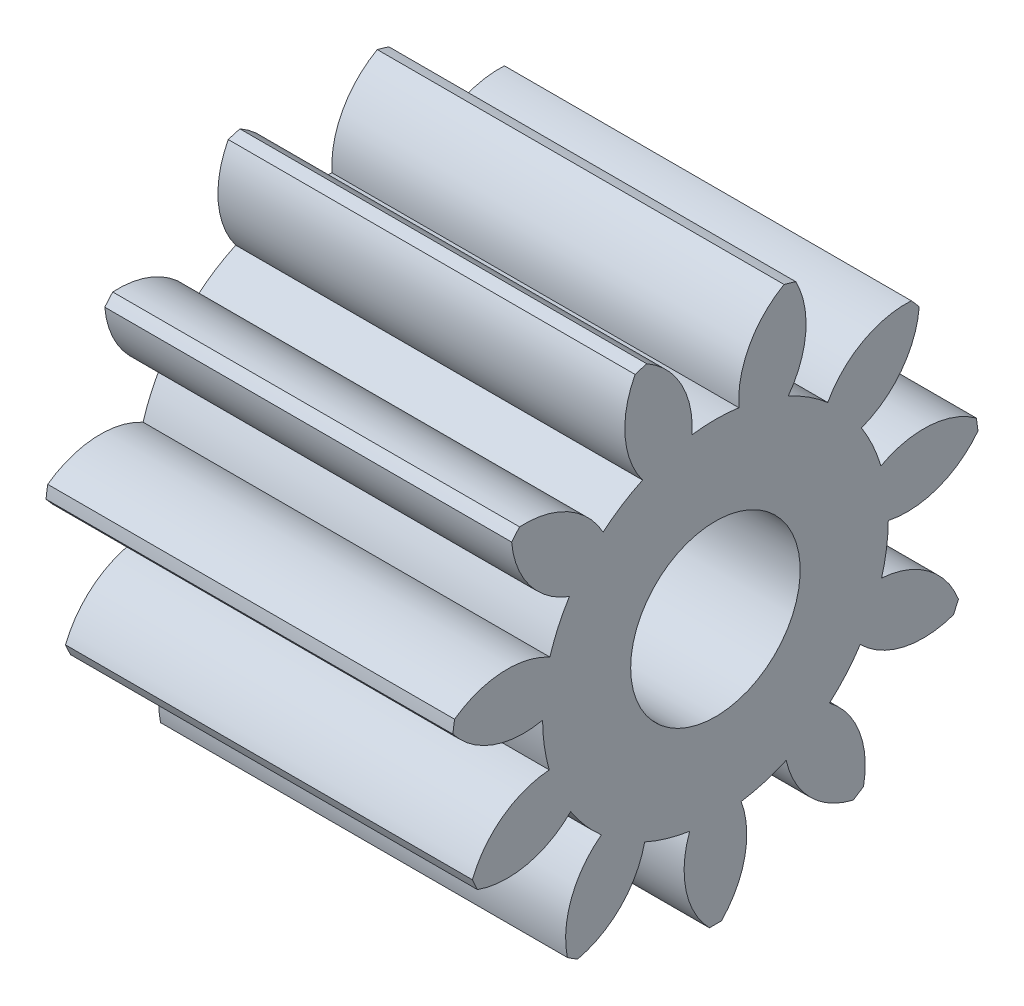
SolidWorks part; units mm, degrees
ref_plane "Plane1" through (0, 0, 0) normal (0, 0, 1) x (1, 0, 0)
ref_plane "Plane2" through (0, 0, 0) normal (0, 1, 0) x (1, 0, 0)
ref_plane "Plane3" through (0, 0, 0) normal (1, 0, 0) x (0, 0, -1)
other "Configuration Table"
sketch "HoldingSke" plane through (0, 0, 0) normal (0, 1, 0) x (1, 0, 0)
  line L0 (0, 0) -> (1.636, -0.318)
  line L1 (-15, 0) -> (100, 0) construction
  line L2 (0, 0) -> (-2.1039, 2.3779)
  line L3 (0, 0) -> (-11.863, 4.5341)
  line L4 (0, 0) -> (8.4773, 1.6478)
  line L5 (0, 0) -> (-46.8476, -17.4728)
  line L6 (0, 0) -> (-4.9738, -3.3558)
  line L7 (-2.1039, 2.3779) -> (8.6586, 51.206)
  line L8 (-76.2, 54.61) -> (-75.7, 54.61)
  line L9 (-71.009, 38.7566) -> (-53.1078, 45.2721)
  line L10 (-76.2, 71.12) -> (104.1128, 71.12)
  line L11 (0, 0) -> (-6, 0)
  line L12 (-76.2, 101.6) -> (-76.177, 101.6)
  line L13 (24.9733, 27.94) -> (52.9518, 28.4284)
  line L14 (24.9733, 27.94) -> (24.9743, 27.94)
  line L15 (24.9733, 27.94) -> (100.4006, 29.5858)
  line L16 (-63.627, -0.6) -> (-12.827, -0.6)
  circle A0 centre (0, 0) radius 1.5
  circle A1 centre (0, 0) radius 2.549
  circle A2 centre (0, 0) radius 37.5
  circle A3 centre (0, 0) radius 1.25
  dimension "MHD" = 5.098
  dimension "Hub_dia" = 75
  dimension "Bore" = 3
  dimension "MBD" = 2.5
  dimension "Num_teeth" = 11
  dimension "Pitch" = 1.6667
  dimension "Overall_len" = 50
  dimension "Show_teeth" = 11
  dimension "Thickness" = 6
  dimension "OAL" = 50.0002
  dimension "T_dim" = 0.5
  dimension "Ap" = 20
  dimension "H" = 19.05
  dimension "Pitch_radius" = 180.3128
  dimension "Width" = 6
  dimension "Backlash" = 0.023
  dimension "Addendum_fac" = 1
  dimension "Dedendum_fac" = 1.25
  dimension "Clearance_fac" = 0.25
  dimension "Dedendum_add" = 0.001
  dimension "Module" = 0.6
sketch "BasProSke" plane through (0, 0, 0) normal (0, 1, 0) x (1, 0, 0)
  line L0 (-10, 0) -> (60, 0) construction
  line L1 (0, 0) -> (0, 3.9)
  line L2 (0, 0) -> (6, 0)
  line L3 (6, 0) -> (6, 3.9)
  line L4 (6, 3.9) -> (0, 3.9)
  dimension "Thickness" = 6
  dimension "Diameter" = 7.8
revolve "Base-Revolve" add sketch "BasProSke" angle 360 about L0
sketch "TooCutSke" plane through (0, 0, 0) normal (1, 0, 0) x (0, 0, -1)
  line L1 (0, 0) -> (0, 107) construction
  line L2 (0, 0) -> (-0.5098, 3.2604) construction
  line L3 (0, 0) -> (-1.8436, 6.2788) construction
  line L4 (-0.5098, 3.2604) -> (-0.9218, 3.1394) construction
  arc A0 (0.3459, 2.5254) -> (-0.3459, 2.5254) centre (0, 0) ccw
  arc A1 (1.0446, 3.7839) -> (-1.0446, 3.7839) centre (0, 0) ccw
  circle A2 centre (0, 0) radius 3.3 construction
  circle A3 centre (0, 0) radius 3.101 construction
  arc A4 (-0.3459, 2.5254) -> (-1.0446, 3.7839) centre (-1.6627, 2.6175) ccw
  arc A5 (1.0446, 3.7839) -> (0.3459, 2.5254) centre (1.6627, 2.6175) ccw
  dimension "Root_dia" = 5.098
  dimension "Overcut_dia" = 7.8508
  dimension "Pitch_dia" = 6.6
  dimension "Base_dia" = 6.202
  dimension "Flank_rad" = 1.32
  dimension "Half_ang" = 16.364
  dimension "Half_CT" = 0.4294
extrude "ToothCut" cut sketch "TooCutSke" along normal through all
fillet "Breaks" [suppressed] radius 0.012
fillet "RootFillets" [suppressed] radius 0.151
pattern_circular "TeethCuts" count 11 over 360 about axis through (0, 0, 0) along (1, 0, 0) of "ToothCut", "RootFillets", "Breaks"
sketch "HubNeaOneSke" plane through (0, 0, 0) normal (-1, 0, 0) x (0, 0, 1)
  circle A0 centre (0, 0) radius 2.549
  dimension "Diameter" = 5.098
extrude "HubNearOne" [suppressed] add sketch "HubNeaOneSke" along normal blind 44.0002
sketch "HubNeaBotSke" plane through (0, 0, 0) normal (-1, 0, 0) x (0, 0, 1)
  circle A0 centre (0, 0) radius 2.549
  dimension "Diameter" = 5.098
extrude "HubNearBoth" [suppressed] add sketch "HubNeaBotSke" along normal blind 22.0001
ref_plane "FarPln" through (6, 0, 0) normal (1, 0, 0) x (0, 0, -1)
sketch "HubFarSke" plane through (6, 0, 0) normal (1, 0, 0) x (0, 0, -1)
  circle A0 centre (0, 0) radius 2.549
  dimension "Diameter" = 5.098
extrude "HubFar" [suppressed] add sketch "HubFarSke" along normal blind 22.0001
sketch "BorSke" plane through (0, 0, 0) normal (1, 0, 0) x (0, 0, -1)
  circle A0 centre (0, 0) radius 1.25
  dimension "Diameter" = 2.5
extrude "Bore" cut sketch "BorSke" along normal mid plane 100.0003
sketch "KeySke" plane through (0, 0, 0) normal (1, 0, 0) x (0, 0, -1)
  line L0 (-0.6, 0) -> (-0.6, 1.75)
  line L1 (-0.6, 1.75) -> (0.6, 1.75)
  line L2 (0.6, 1.75) -> (0.6, 0)
  line L3 (0, 0) -> (0, 34) construction
  line L4 (-0.6, 0) -> (0.6, 0)
  dimension "Offset" = 1.75
  dimension "Width" = 1.2
extrude "Keyway" [suppressed] cut sketch "KeySke" along normal mid plane 100.0003
pattern_circular "Keyway2" [suppressed] count 2 every 90 about axis through (-10, 0, 0) along (1, 0, 0)
equation "' \"Module@HoldingSke\" = 6.35"
equation "' \"Num_teeth@HoldingSke\" = 12"
equation "' \"Ap@HoldingSke\" =  20"
equation "' \"Ap@HoldingSke\" = 20"
equation "' \"Width@HoldingSke\" = 0.5 * 25.4"
equation "' \"Hub_dia@HoldingSke\"= 1 * 25.4"
equation "' \"Hub_dia@HoldingSke\" = 1 * 25.4"
equation "' \"Overall_len@HoldingSke\" = 1.0 * 25.4"
equation "' \"Bore@HoldingSke\" = 0.75 * 25.4"
equation "' \"T_dim@HoldingSke\" = 0.1 * 25.4"
equation "' \"Width@KeySke\" = 0.25 * 25.4"
equation "' \"Show_teeth@HoldingSke\" = 13"
equation "' \"Backlash@HoldingSke\" = 0.009 * 25.4"
equation "' \"Addendum_fac@HoldingSke\" = 1.0"
equation "' \"Dedendum_fac@HoldingSke\" = 1.25"
equation "' \"Dedendum_add@HoldingSke\" = 0.00005 * 25.4"
equation "' \"Clearance_fac@HoldingSke\" = 0.25"
equation "\"Pitch@HoldingSke\" = 1 / \"Module@HoldingSke\""
equation "\"Overcut_dia@TooCutSke\" = (\"Num_teeth@HoldingSke\" + 2 * \"Addendum_fac@HoldingSke\") / \"Pitch@HoldingSke\" + 0.002 * 25.4"
equation "\"Pitch_dia@TooCutSke\" = \"Num_teeth@HoldingSke\" / \"Pitch@HoldingSke\""
equation "\"Base_dia@TooCutSke\" = \"Num_teeth@HoldingSke\" / \"Pitch@HoldingSke\" * cos((\"Ap@HoldingSke\"  * 3.14159265 / 180))"
equation "\"Root_dia@TooCutSke\" = (\"Num_teeth@HoldingSke\" + 2) / \"Pitch@HoldingSke\" - 2 * (\"Addendum_fac@HoldingSke\" + \"Dedendum_fac@HoldingSke\") / \"Pitch@HoldingSke\" - \"Dedendum_add@HoldingSke\" * 2"
equation "\"Half_ang@TooCutSke\" = 180 / \"Num_teeth@HoldingSke\""
equation "\"Half_CT@TooCutSke\" = \"Num_teeth@HoldingSke\" / \"Pitch@HoldingSke\" * sin((3.14159265 / 2 / \"Num_teeth@HoldingSke\")) / 2 - 7 * \"Backlash@HoldingSke\" / 4"
equation "\"Flank_rad@TooCutSke\" = \"Num_teeth@HoldingSke\" / \"Pitch@HoldingSke\" / 5"
equation "\"Radius@RootFillets\" = \"Clearance_fac@HoldingSke\" / \"Pitch@HoldingSke\" + \"Dedendum_add@HoldingSke\""
equation "\"Break_rad@Breaks\" = 0.02 / \"Pitch@HoldingSke\""
equation "\"Thickness@HoldingSke\" = \"Width@HoldingSke\""
equation "\"OAL@HoldingSke\" = \"Thickness@HoldingSke\""
equation "\"MHD@HoldingSke\" = (\"Num_teeth@HoldingSke\" + 2) / \"Pitch@HoldingSke\" - 2 * (\"Addendum_fac@HoldingSke\" + \"Dedendum_fac@HoldingSke\")  / \"Pitch@HoldingSke\" - \"Dedendum_add@HoldingSke\" * 2"
equation "\"MBD@HoldingSke\" = (\"Num_teeth@HoldingSke\" + 2) / \"Pitch@HoldingSke\" - 2 * (\"Addendum_fac@HoldingSke\" + \"Dedendum_fac@HoldingSke\")  / \"Pitch@HoldingSke\" - \"Dedendum_add@HoldingSke\" * 2 - 0.002 * 25.4"
equation "\"MHD@HoldingSke\" = ((sgn( \"MHD@HoldingSke\" - \"Hub_dia@HoldingSke\" )-1)*( \"MHD@HoldingSke\" - \"Hub_dia@HoldingSke\" ))/-2+ \"Hub_dia@HoldingSke\""
equation "\"OAL@HoldingSke\" = ((sgn( \"OAL@HoldingSke\" - \"Overall_len@HoldingSke\" )+1)*( \"OAL@HoldingSke\" - \"Overall_len@HoldingSke\" ))/2 + \"Overall_len@HoldingSke\" + 0.000002 * 25.4"
equation "\"Num_teeth@TeethCuts\" = int( \"Show_teeth@HoldingSke\" ) + 1"
equation "\"Num_teeth@TeethCuts\" = ((sgn( \"Num_teeth@TeethCuts\" - \"Num_teeth@HoldingSke\" )-1)*( \"Num_teeth@TeethCuts\" - \"Num_teeth@HoldingSke\" ))/-2+ \"Num_teeth@HoldingSke\""
equation "\"Num_teeth@TeethCuts\" = ((sgn( \"Num_teeth@TeethCuts\" - 2.0)+1)*( \"Num_teeth@TeethCuts\" - 2.0))/2 +2.0"
equation "\"Angle@TeethCuts\" = 360.0 / \"Num_teeth@HoldingSke\""
equation "\"Diameter@BasProSke\" = (\"Num_teeth@HoldingSke\" + 2 * \"Addendum_fac@HoldingSke\") / \"Pitch@HoldingSke\""
equation "\"Thickness@BasProSke\"  = \"Thickness@HoldingSke\""
equation "' \"Fillet_rad@BasProSke\" =  \"Thickness@HoldingSke\" * 0.05"
equation "' \"Fillet_rad@BasProSke\" = \"Thickness@HoldingSke\" * 0.05"
equation "\"MHD@HoldingSke\" = ((sgn( \"MHD@HoldingSke\" - \"Root_dia@TooCutSke\" )-1)*( \"MHD@HoldingSke\" - \"Root_dia@TooCutSke\" ))/-2+ \"Root_dia@TooCutSke\""
equation "\"Diameter@HubNeaOneSke\" = \"MHD@HoldingSke\""
equation "\"Length@HubNearOne\" = \"OAL@HoldingSke\" - \"Thickness@BasProSke\""
equation "\"Diameter@HubNeaBotSke\" = \"MHD@HoldingSke\""
equation "\"Length@HubNearBoth\" = ( \"OAL@HoldingSke\" - \"Thickness@BasProSke\" ) / 2.0"
equation "\"Thickness@FarPln\" = \"Thickness@BasProSke\""
equation "\"Diameter@HubFarSke\" = \"MHD@HoldingSke\""
equation "\"Length@HubFar\" = ( \"OAL@HoldingSke\" - \"Thickness@BasProSke\" ) / 2.0"
equation "\"Diameter@BorSke\" = \"MBD@HoldingSke\""
equation "\"D1@Bore\" = \"OAL@HoldingSke\" * 2.0"
equation "\"D1@Keyway\" = \"OAL@HoldingSke\" * 2.0"
equation "\"Offset@KeySke\" = \"T_dim@HoldingSke\" + \"MBD@HoldingSke\" / 2.0"
